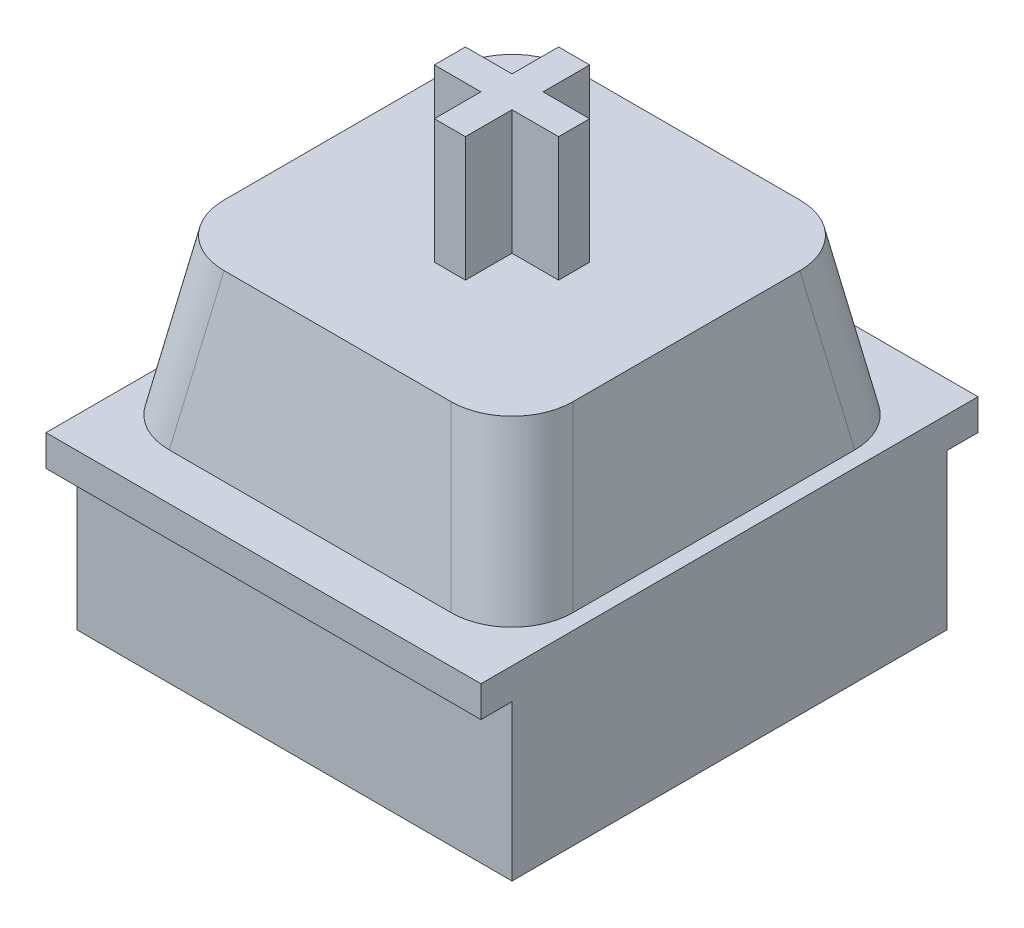
SolidWorks part; units mm, degrees
ref_plane "Front Plane" through (0, 0, 0) normal (0, 0, 1) x (1, 0, 0)
ref_plane "Top Plane" through (0, 0, 0) normal (0, 1, 0) x (1, 0, 0)
ref_plane "Right Plane" through (0, 0, 0) normal (1, 0, 0) x (0, 0, -1)
sketch "Sketch1" plane through (0, 0, 0) normal (0, 1, 0) x (1, 0, 0)
  line L1 (-7, -7) -> (7, -7)
  line L2 (-7, -7) -> (-7, 7)
  line L3 (-7, 7) -> (7, 7)
  line L4 (7, -7) -> (7, 7)
  line L5 (-7, -7) -> (7, 7) construction
  line L6 (-7, 7) -> (7, -7) construction
  point P1 (0, 0)
  dimension "D1" = 14
  dimension "D2" = 14
extrude "Boss-Extrude1" add sketch "Sketch1" along normal blind 5
sketch "Sketch2" plane through (0, 5, 0) normal (0, 1, 0) x (1, 0, 0)
  line L0 (-7, 7) -> (-7, -7) construction
  line L1 (-7, -8) -> (7, -8)
  line L2 (-7, -8) -> (-7, 8)
  line L3 (-7, 8) -> (7, 8)
  line L4 (7, -8) -> (7, 8)
  line L5 (-7, -8) -> (7, 8) construction
  line L6 (-7, 8) -> (7, -8) construction
  line L7 (7, 7) -> (-7, 7) construction
  point P0 (0, 0)
  dimension "D1" = 0
  dimension "D2" = 1
extrude "Boss-Extrude2" add sketch "Sketch2" along normal blind 1
sketch "Sketch3" plane through (0, 6, 0) normal (0, 1, 0) x (1, 0, 0)
  line L1 (-6.5, -6.5) -> (6.5, -6.5)
  line L2 (-6.5, -6.5) -> (-6.5, 6.5)
  line L3 (-6.5, 6.5) -> (6.5, 6.5)
  line L4 (6.5, -6.5) -> (6.5, 6.5)
  line L5 (-6.5, -6.5) -> (6.5, 6.5) construction
  line L6 (-6.5, 6.5) -> (6.5, -6.5) construction
  point P0 (0, 0)
  dimension "D1" = 13
  dimension "D2" = 13
extrude "Boss-Extrude3" add sketch "Sketch3" along normal blind 5 draft 10
sketch "Sketch4" plane through (0, 11, 0) normal (0, 1, 0) x (1, 0, 0)
  line L0 (0.5, -0.5) -> (2, -0.5)
  line L5 (-0.5, -0.5) -> (0.5, 0.5) construction
  line L6 (-0.5, 0.5) -> (0.5, -0.5) construction
  line L7 (2, -0.5) -> (2, 0.5)
  line L8 (2, 0.5) -> (0.5, 0.5)
  line L9 (-0.5, 0.5) -> (-2, 0.5)
  line L10 (-2, 0.5) -> (-2, -0.5)
  line L11 (-2, -0.5) -> (-0.5, -0.5)
  line L12 (-0.5, -0.5) -> (-0.5, -2)
  line L13 (-0.5, -2) -> (0.5, -2)
  line L14 (0.5, -2) -> (0.5, -0.5)
  line L15 (0.5, 0.5) -> (0.5, 2)
  line L16 (0.5, 2) -> (-0.5, 2)
  line L17 (-0.5, 2) -> (-0.5, 0.5)
  point P0 (0, 0)
  dimension "D1" = 4
  dimension "D2" = 1
extrude "Boss-Extrude4" add sketch "Sketch4" along normal blind 4
sketch "Sketch5" plane through (0, 0, 0) normal (0, -1, 0) x (1, 0, 0)
  circle A0 centre (0, 0) radius 1.75
extrude "Boss-Extrude5" add sketch "Sketch5" along normal blind 3 contours A0
sketch "Sketch6" plane through (0, 0, 0) normal (0, -1, 0) x (1, 0, 0)
  line L0 (7, 7) -> (7, -7) construction
  line L1 (7, -7) -> (-7, -7) construction
  line L2 (-7, -7) -> (-7, -8) construction
  line L3 (7, -7) -> (-7, -7) construction
  circle A0 centre (2.25, -5) radius 0.75
  circle A1 centre (-3.5, -2.75) radius 0.75
  dimension "D5" = 1.5
  dimension "D6" = 1.5
  dimension "D1" = 4.75
  dimension "D2" = 2
  dimension "D3" = 3.5
  dimension "D4" = 4.25
extrude "Boss-Extrude6" add sketch "Sketch6" along normal blind 3
fillet "Fillet1" radius 2 4 edges at (6.0592, 8.5, -6.0592) (6.0592, 8.5, 6.0592) (-6.0592, 8.5, -6.0592) (-6.0592, 8.5, 6.0592)
